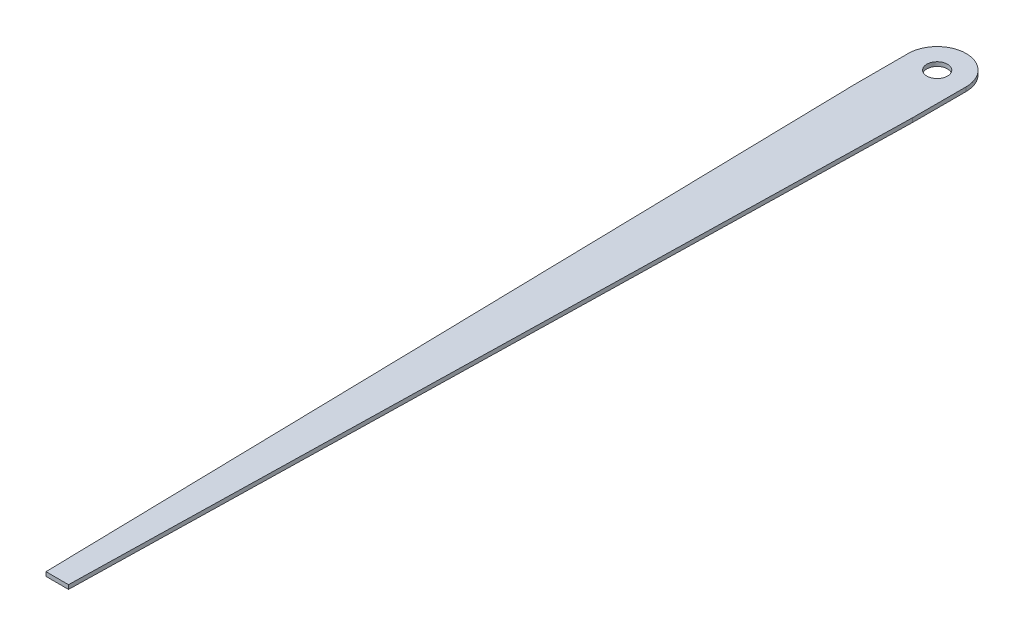
SolidWorks part; units mm, degrees
ref_plane "Front Plane" through (0, 0, 0) normal (0, 0, 1) x (1, 0, 0)
ref_plane "Top Plane" through (0, 0, 0) normal (0, 1, 0) x (1, 0, 0)
ref_plane "Right Plane" through (0, 0, 0) normal (1, 0, 0) x (0, 0, -1)
sketch "Sketch1" plane through (0, 0, 0) normal (0, 1, 0) x (1, 0, 0)
  line L0 (4.275, 200) -> (9.725, 200)
  line L1 (4.275, 0) -> (9.725, 0)
  line L8 (4.275, 0) -> (9.725, 0)
  line L11 (14, 200) -> (0, 200)
  line L13 (9.725, 0) -> (14, 200)
  line L14 (4.275, 0) -> (0, 200)
extrude "Boss-Extrude1" add sketch "Sketch1" along normal blind 1 contours L14 L1 L13 L11 L0
sketch "Sketch2" plane through (0, 0, 0) normal (0, -1, 0) x (1, 0, 0)
  line L0 (0, -200) -> (0, 0) construction
  line L5 (0, -200) -> (14, -200)
  line L6 (0, -200) -> (0, -213)
  line L8 (14, -200) -> (14, -213)
  circle A2 centre (7, -213) radius 2.5
  arc A3 (0, -213) -> (14, -213) centre (7, -213) ccw
  dimension "D1" = 5
  dimension "D2" = 7
  dimension "D3" = 213
extrude "Boss-Extrude2" add sketch "Sketch2" against normal up to surface (1 mm away) contours A3 L8 L5 L6 | A2 up to face at (7, 1, -100)
